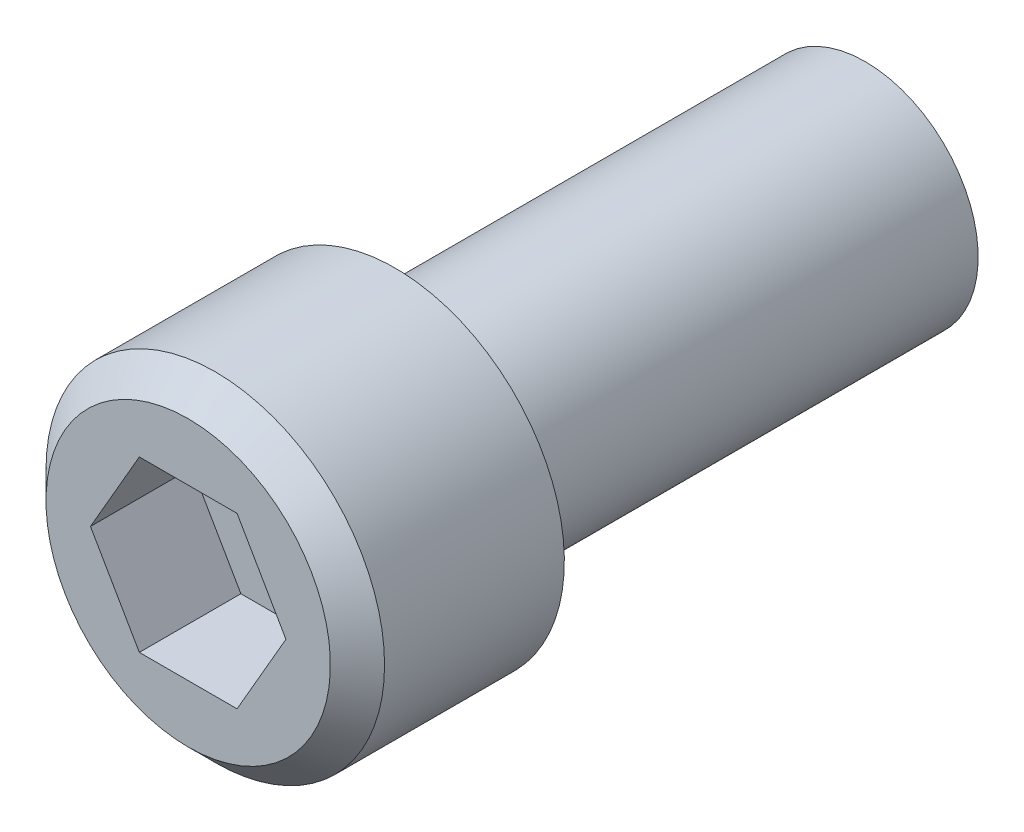
SolidWorks part; units mm, degrees
ref_plane "前视基准面" through (0, 0, 0) normal (0, 0, 1) x (1, 0, 0)
ref_plane "上视基准面" through (0, 0, 0) normal (0, 1, 0) x (1, 0, 0)
ref_plane "右视基准面" through (0, 0, 0) normal (1, 0, 0) x (0, 0, -1)
sketch "草图1" plane through (0, 0, 0) normal (1, 0, 0) x (0, 0, -1)
  line L0 (0, 0) -> (0, 4.5)
  line L1 (0, 4.5) -> (5.5, 4.5)
  line L2 (5.5, 4.5) -> (5.5, 3)
  line L3 (5.5, 3) -> (18, 3)
  line L4 (18, 3) -> (18, 0)
  line L5 (18, 0) -> (0, 0) construction
  dimension "M" = 6
  dimension "D" = 9
  dimension "H" = 5.5
  dimension "L" = 18
sketch "草图2" plane through (0, 0, 0) normal (1, 0, 0) x (0, 0, -1)
  line L0 (0, 0) -> (0, 4.5) construction
  line L1 (0, 4.5) -> (5.5, 4.5) construction
  line L2 (5.5, 4.5) -> (5.5, 3) construction
  line L3 (5.5, 3) -> (18, 3) construction
  line L4 (18, 3) -> (18, 0) construction
  line L5 (0, 0) -> (0, 4.5)
  line L6 (0, 4.5) -> (5.5, 4.5)
  line L7 (5.5, 4.5) -> (5.5, 3)
  line L8 (5.5, 3) -> (18, 3)
  line L9 (18, 3) -> (18, 0)
  line L10 (0, 0) -> (18, 0)
revolve "旋转1" add sketch "草图2" angle 360 mid plane about L10
cosmetic thread "装饰螺纹线1" parameters "D2"=5.9
chamfer "倒角1" distance 0.72 angle 45 1 edges at (0, -4.5, 0)
sketch "草图3" plane through (0, 0, 0) normal (0, 0, 1) x (1, 0, 0)
  line L1 (2.5981, 0) -> (1.299, 2.25)
  line L2 (1.299, 2.25) -> (-1.299, 2.25)
  line L3 (-1.299, 2.25) -> (-2.5981, 0)
  line L4 (-2.5981, 0) -> (-1.299, -2.25)
  line L5 (-1.299, -2.25) -> (1.299, -2.25)
  line L6 (1.299, -2.25) -> (2.5981, 0)
  circle A0 centre (0, 0) radius 2.25 construction
  dimension "D1" = 4.5
extrude "切除-拉伸1" cut sketch "草图3" against normal blind 2.7
